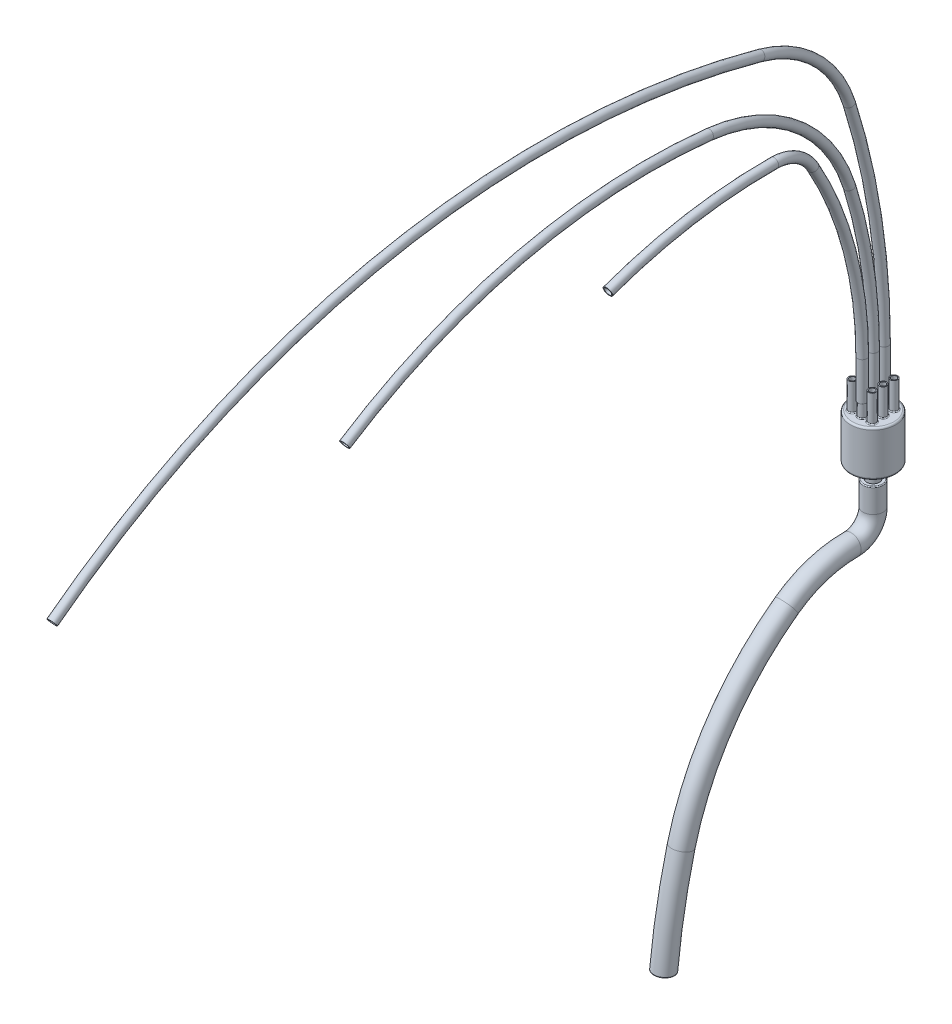
SolidWorks part; units mm, degrees
ref_plane "Alzado" through (0, 0, 0) normal (0, 0, 1) x (1, 0, 0)
ref_plane "Planta" through (0, 0, 0) normal (0, 1, 0) x (1, 0, 0)
ref_plane "Vista lateral" through (0, 0, 0) normal (1, 0, 0) x (0, 0, -1)
sketch "Croquis1" plane through (0, 0, 0) normal (0, 1, 0) x (1, 0, 0)
  circle A0 centre (0, 0) radius 25
  dimension "D1" = 50
extrude "Extruir1" add sketch "Croquis1" along normal mid plane 50
sketch "Croquis2" plane through (0, -25, 0) normal (0, -1, 0) x (1, 0, 0)
  circle A0 centre (0, 0) radius 7
  dimension "D1" = 14
extrude "Extruir2" add sketch "Croquis2" along normal blind 40
sketch "Croquis3" plane through (0, 25, 0) normal (0, 1, 0) x (1, 0, 0)
  line L0 (-11, 0) -> (11, 0) construction
  line L1 (-11, 12) -> (11, 12) construction
  line L2 (-11, -12) -> (11, -12) construction
  circle A0 centre (0, 0) radius 4
  circle A1 centre (-11, 0) radius 4
  circle A2 centre (11, 0) radius 4
  circle A3 centre (-11, 12) radius 4
  circle A5 centre (0, 12) radius 4
  circle A6 centre (11, 12) radius 4
  circle A7 centre (-11, -12) radius 4
  circle A8 centre (11, -12) radius 4
  circle A9 centre (0, -12) radius 4
  dimension "D1" = 8
  dimension "D2" = 22
extrude "Extruir3" add sketch "Croquis3" along normal blind 30
fillet "Redondeo1" radius 2 2 edges at (0, -25, 25) (0, 25, 25)
shell "Vaciado1" thickness 1
fillet "Redondeo2" radius 1 10 edges at (0, -25, 7) (11, 25, 16) (0, 25, 16) (-11, 25, -8) (11, 25, 4) (0, 25, 4) (-11, 25, 4) (0, 25, -8) (11, 25, -8) (-11, 25, 16)
sketch "Croquis4" plane through (0, 0, 0) normal (1, 0, 0) x (0, 0, -1)
  line L0 (0, 40) -> (0, 82.3569)
  arc A0 (0, 82.3569) -> (-26.2107, 251.8109) centre (-560.8719, 82.3569) ccw
  arc A1 (-26.2107, 251.8109) -> (-181.3018, 378.7036) centre (-200.989, 196.4171) ccw
  arc A2 (-181.3018, 378.7036) -> (-583.2637, 283.2178) centre (-247.6629, -235.7417) ccw
  dimension "D1" = 40
sketch "Croquis5" plane through (0, 0, 0) normal (1, 0, 0) x (0, 0, -1)
  line L0 (-12, 40) -> (-12, 82.2054)
  arc A0 (-12, 82.2054) -> (-66.629, 290.3482) centre (-435.8384, 82.2054) ccw
  arc A1 (-66.629, 290.3482) -> (-109.2835, 315.5532) centre (-109.7769, 266.0235) ccw
  arc A2 (-109.2835, 315.5532) -> (-292.7668, 284.2878) centre (-114.4974, -207.8747) ccw
  dimension "D1" = 40
sketch "Croquis6" plane through (0, 0, 0) normal (1, 0, 0) x (0, 0, -1)
  line L0 (12, 40) -> (12, 82.3569)
  arc A0 (12, 82.3569) -> (-26.4389, 331.227) centre (-812.8664, 82.3569) ccw
  arc A1 (-26.4389, 331.227) -> (-124.7455, 425.968) centre (-162.8456, 288.0602) ccw
  arc A2 (-124.7455, 425.968) -> (-906.2557, 274.6508) centre (-363.1015, -436.7881) ccw
ref_plane "Plano1" through (0, 40, 12) normal (0, 1, 0) x (-1, 0, 0)
sketch "Croquis7" plane through (0, 40, 12) normal (0, 1, 0) x (-1, 0, 0)
  circle A0 centre (0, 0) radius 5
  dimension "D1" = 10
sweep "Barrer1" add profiles "Croquis7" path "Croquis5"
sketch "Croquis8" plane through (0, 40, 12) normal (0, 1, 0) x (-1, 0, 0)
  circle A0 centre (0, -12) radius 5
  dimension "D1" = 10
sweep "Barrer2" add profiles "Croquis8" path "Croquis4"
sketch "Croquis9" plane through (0, 40, 12) normal (0, 1, 0) x (-1, 0, 0)
  circle A0 centre (0, -24) radius 5
  dimension "D1" = 10
sweep "Barrer3" add profiles "Croquis9" path "Croquis6"
shell "Vaciado2" thickness 1
shell "Vaciado3" thickness 1
shell "Vaciado4" thickness 1
sketch "Croquis10" plane through (0, 0, 0) normal (1, 0, 0) x (0, 0, -1)
  line L0 (0, -40.9768) -> (0, -67.5571)
  line L1 (0, -65) -> (0, -26) construction
  arc A0 (0, -67.5571) -> (-24.1896, -91.6199) centre (-24.0632, -67.5571) cw
  arc A1 (-24.1896, -91.6199) -> (-95.3684, -114.5141) centre (-24.8211, -211.7521) ccw
  arc A2 (-95.3684, -114.5141) -> (-211.8225, -285.9998) centre (83.8015, -361.4708) ccw
  arc A3 (-211.8225, -285.9998) -> (-231.2883, -396.1499) centre (511.0055, -470.5332) ccw
ref_plane "Plano2" through (0, -40.9768, 0) normal (0, -1, 0) x (1, 0, 0)
sketch "Croquis11" plane through (0, -40.9768, 0) normal (0, -1, 0) x (1, 0, 0)
  circle A0 centre (0, 0) radius 11
  dimension "D1" = 22
sweep "Barrer4" add profiles "Croquis11" path "Croquis10"
shell "Vaciado5" thickness 4
fillet "Redondeo3" radius 1 2 edges at (0, -397.2467, 220.3431) (0, -40.9768, -11)
